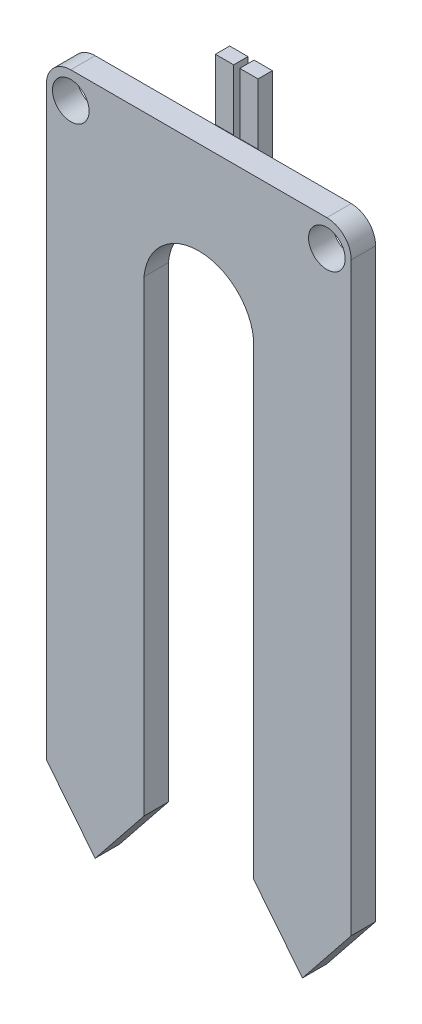
SolidWorks part; units mm, degrees
ref_plane "Front Plane" through (0, 0, 0) normal (0, 0, 1) x (1, 0, 0)
ref_plane "Top Plane" through (0, 0, 0) normal (0, 1, 0) x (1, 0, 0)
ref_plane "Right Plane" through (0, 0, 0) normal (1, 0, 0) x (0, 0, -1)
sketch "Sketch1" plane through (0, 0, 0) normal (0, 0, 1) x (1, 0, 0)
  line L0 (-31.9569, -21.6667) -> (-31.9569, 26.3333)
  line L1 (-29.9569, 28.3333) -> (-8.9569, 28.3333)
  line L2 (-6.9569, 26.3333) -> (-6.9569, -21.6667)
  line L5 (-14.9569, -21.6667) -> (-14.9569, 16.6279)
  line L7 (-23.9569, 16.6279) -> (-23.9569, -21.6667)
  line L10 (-23.9569, 28.3333) -> (-23.9569, 16.6279) construction
  line L11 (-27.9569, -21.6667) -> (-27.9569, -26.6667) construction
  line L12 (-31.9569, -21.6667) -> (-23.9569, -21.6667) construction
  line L13 (-14.9569, -21.6667) -> (-6.9569, -21.6667) construction
  line L14 (-10.9569, -21.6667) -> (-10.9569, -26.6667) construction
  line L15 (-31.9569, -21.6667) -> (-27.9569, -26.6667)
  line L16 (-27.9569, -26.6667) -> (-23.9569, -21.6667)
  line L17 (-14.9569, -21.6667) -> (-10.9569, -26.6667)
  line L18 (-10.9569, -26.6667) -> (-6.9569, -21.6667)
  arc A0 (-8.9569, 28.3333) -> (-6.9569, 26.3333) centre (-8.9569, 26.3333) cw
  arc A1 (-31.9569, 26.3333) -> (-29.9569, 28.3333) centre (-29.9569, 26.3333) cw
  arc A2 (-23.9569, 16.6279) -> (-14.9569, 16.6279) centre (-19.4569, 16.2026) cw
  point P15 (-6.9569, 28.3333)
  point P18 (-31.9569, 28.3333)
  point P20 (-23.4464, 16.6279)
  point P21 (-9.7982, 17.2627)
  point P22 (-9.9569, 16.6279)
  dimension "D8" = 2
  dimension "D1" = 50
  dimension "D2" = 25
  dimension "D3" = 50
  dimension "D4" = 5
  dimension "D5" = 8
  dimension "D6" = 8
  dimension "D7" = 5
  dimension "D9" = 8
extrude "Boss-Extrude1" add sketch "Sketch1" along normal blind 2
sketch "Sketch2" plane through (0, 0, 0) normal (0, 0, -1) x (-1, 0, 0)
  line L0 (6.9569, -21.6667) -> (6.9569, 26.3333) construction
  line L1 (31.9569, 26.3333) -> (31.9569, -21.6667) construction
  circle A0 centre (8.9569, 26.1469) radius 1.5
  circle A1 centre (29.9569, 26.1469) radius 1.5
  dimension "D1" = 3
  dimension "D2" = 3
  dimension "D3" = 2
  dimension "D4" = 2
extrude "Cut-Extrude1" cut sketch "Sketch2" against normal up to next
sketch "Sketch3" plane through (0, 0, 0) normal (0, 0, -1) x (-1, 0, 0)
  line L0 (19.4251, 27.5381) -> (19.4251, 26.0381)
  line L1 (17.4251, 27.5381) -> (18.9251, 27.5381)
  line L2 (17.4251, 27.5381) -> (17.4251, 26.0381)
  line L3 (17.4251, 26.0381) -> (18.9251, 26.0381)
  line L4 (18.9251, 27.5381) -> (18.9251, 26.0381)
  line L5 (19.4251, 27.5381) -> (20.9251, 27.5381)
  line L6 (20.9251, 27.5381) -> (20.9251, 26.0381)
  line L7 (19.4251, 26.0381) -> (20.9251, 26.0381)
  dimension "D1" = 1.5
  dimension "D2" = 1.5
  dimension "D3" = 2
extrude "Boss-Extrude2" add sketch "Sketch3" along normal blind 2
sketch "Sketch6" plane through (0, 27.5381, 0) normal (0, 1, 0) x (1, 0, 0)
  line L0 (-18.9251, 2) -> (-18.9251, 0.8285)
  line L1 (-20.9251, 2) -> (-19.4251, 2)
  line L2 (-20.9251, 2) -> (-20.9251, 0.8285)
  line L3 (-20.9251, 0.8285) -> (-19.4251, 0.8285)
  line L4 (-19.4251, 2) -> (-19.4251, 0.8285)
  line L5 (-18.9251, 2) -> (-17.4251, 2)
  line L6 (-17.4251, 2) -> (-17.4251, 0.8285)
  line L7 (-18.9251, 0.8285) -> (-17.4251, 0.8285)
  line L8 (-19.4251, 2) -> (-19.4251, 0) construction
  point P5 (-19.4251, 2)
  dimension "D1" = 2
extrude "Boss-Extrude5" add sketch "Sketch6" along normal blind 5
fillet "Fillet1" radius 0.2 2 edges at (-18.1751, 26.0381, -2) (-20.1751, 26.0381, -2)
sketch "Sketch7" plane through (0, 0, 0) normal (0, 0, -1) x (-1, 0, 0)
  line L0 (6.9569, 16.8604) -> (31.9569, 16.8604) construction
  line L1 (6.9569, -21.6667) -> (6.9569, 26.3333) construction
  line L2 (31.9569, 26.3333) -> (31.9569, -21.6667) construction
  line L3 (8.9569, 16.8604) -> (8.9569, 15.5723)
  line L5 (12.9569, -19.2207) -> (12.9569, -16.5552)
  line L6 (8.9569, 16.8604) -> (12.9569, 16.8604)
  line L28 (7.9941, 15.5723) -> (8.9569, 15.5723)
  line L30 (13.997, 13.4448) -> (12.9569, 13.4448)
  line L47 (7.9941, 9.5723) -> (8.9569, 9.5723)
  line L48 (13.997, 7.4448) -> (12.9569, 7.4448)
  line L49 (7.9941, 3.5723) -> (8.9569, 3.5723)
  line L50 (13.997, 1.4448) -> (12.9569, 1.4448)
  line L51 (7.9941, -2.4277) -> (8.9569, -2.4277)
  line L52 (13.997, -4.5552) -> (12.9569, -4.5552)
  line L53 (7.9941, -8.4277) -> (8.9569, -8.4277)
  line L54 (13.997, -10.5552) -> (12.9569, -10.5552)
  line L55 (7.9941, -14.4277) -> (8.9569, -14.4277)
  line L56 (13.997, -16.5552) -> (12.9569, -16.5552)
  line L57 (8.9569, 13.4448) -> (8.9569, 9.5723)
  line L58 (12.9569, 15.5723) -> (12.9569, 16.8604)
  line L59 (12.9569, 9.5723) -> (12.9569, 13.4448)
  line L60 (8.9569, 7.4448) -> (8.9569, 3.5723)
  line L61 (8.9569, 1.4448) -> (8.9569, -2.4277)
  line L62 (12.9569, 3.5723) -> (12.9569, 7.4448)
  line L63 (8.9569, -4.5552) -> (8.9569, -8.4277)
  line L64 (12.9569, -2.4277) -> (12.9569, 1.4448)
  line L65 (12.9569, -8.4277) -> (12.9569, -4.5552)
  line L66 (8.9569, -10.5552) -> (8.9569, -14.4277)
  line L67 (8.9569, -16.5552) -> (8.9569, -19.2207)
  line L68 (12.9569, -14.4277) -> (12.9569, -10.5552)
  line L69 (8.9569, -16.5552) -> (7.9941, -16.5552)
  line L70 (12.9569, -14.4277) -> (13.997, -14.4277)
  line L71 (8.9569, -10.5552) -> (7.9941, -10.5552)
  line L72 (12.9569, -8.4277) -> (13.997, -8.4277)
  line L73 (8.9569, -4.5552) -> (7.9941, -4.5552)
  line L74 (12.9569, -2.4277) -> (13.997, -2.4277)
  line L75 (8.9569, 1.4448) -> (7.9941, 1.4448)
  line L76 (12.9569, 3.5723) -> (13.997, 3.5723)
  line L77 (8.9569, 7.4448) -> (7.9941, 7.4448)
  line L78 (12.9569, 9.5723) -> (13.997, 9.5723)
  line L79 (8.9569, 13.4448) -> (7.9941, 13.4448)
  line L80 (12.9569, 15.5723) -> (13.997, 15.5723)
  line L81 (30.997, -16.5552) -> (29.9569, -16.5552)
  line L82 (29.9569, -19.2207) -> (29.9569, -16.5552)
  line L83 (25.9569, -16.5552) -> (25.9569, -19.2207)
  line L84 (25.9569, -16.5552) -> (24.9941, -16.5552)
  line L85 (24.9941, -14.4277) -> (25.9569, -14.4277)
  line L86 (25.9569, -10.5552) -> (25.9569, -14.4277)
  line L87 (25.9569, -10.5552) -> (24.9941, -10.5552)
  line L88 (24.9941, -8.4277) -> (25.9569, -8.4277)
  line L89 (25.9569, -4.5552) -> (25.9569, -8.4277)
  line L90 (25.9569, -4.5552) -> (24.9941, -4.5552)
  line L91 (24.9941, -2.4277) -> (25.9569, -2.4277)
  line L92 (25.9569, 1.4448) -> (25.9569, -2.4277)
  line L93 (25.9569, 1.4448) -> (24.9941, 1.4448)
  line L94 (24.9941, 3.5723) -> (25.9569, 3.5723)
  line L95 (25.9569, 7.4448) -> (25.9569, 3.5723)
  line L96 (25.9569, 7.4448) -> (24.9941, 7.4448)
  line L97 (24.9941, 9.5723) -> (25.9569, 9.5723)
  line L98 (25.9569, 13.4448) -> (25.9569, 9.5723)
  line L99 (25.9569, 13.4448) -> (24.9941, 13.4448)
  line L100 (24.9941, 15.5723) -> (25.9569, 15.5723)
  line L101 (25.9569, 16.8604) -> (25.9569, 15.5723)
  line L102 (25.9569, 16.8604) -> (29.9569, 16.8604)
  line L103 (29.9569, 15.5723) -> (29.9569, 16.8604)
  line L104 (29.9569, 15.5723) -> (30.997, 15.5723)
  line L105 (30.997, 13.4448) -> (29.9569, 13.4448)
  line L106 (29.9569, 9.5723) -> (29.9569, 13.4448)
  line L107 (29.9569, 9.5723) -> (30.997, 9.5723)
  line L108 (30.997, 7.4448) -> (29.9569, 7.4448)
  line L109 (29.9569, 3.5723) -> (29.9569, 7.4448)
  line L110 (29.9569, 3.5723) -> (30.997, 3.5723)
  line L111 (30.997, 1.4448) -> (29.9569, 1.4448)
  line L112 (29.9569, -2.4277) -> (29.9569, 1.4448)
  line L113 (29.9569, -2.4277) -> (30.997, -2.4277)
  line L114 (30.997, -4.5552) -> (29.9569, -4.5552)
  line L115 (29.9569, -8.4277) -> (29.9569, -4.5552)
  line L116 (29.9569, -8.4277) -> (30.997, -8.4277)
  line L117 (30.997, -10.5552) -> (29.9569, -10.5552)
  line L118 (29.9569, -14.4277) -> (29.9569, -10.5552)
  line L119 (29.9569, -14.4277) -> (30.997, -14.4277)
  arc A0 (8.9569, -19.2207) -> (12.9569, -19.2207) centre (10.9569, -19.2207) ccw
  arc A1 (7.9941, 15.5723) -> (7.9941, 13.4448) centre (9.0578, 14.5086) ccw
  arc A2 (13.997, 15.5723) -> (13.997, 13.4448) centre (12.9333, 14.5086) cw
  arc A3 (13.997, 9.5723) -> (13.997, 7.4448) centre (12.9333, 8.5086) cw
  arc A4 (7.9941, 9.5723) -> (7.9941, 7.4448) centre (9.0578, 8.5086) ccw
  arc A5 (13.997, 3.5723) -> (13.997, 1.4448) centre (12.9333, 2.5086) cw
  arc A6 (7.9941, 3.5723) -> (7.9941, 1.4448) centre (9.0578, 2.5086) ccw
  arc A7 (13.997, -2.4277) -> (13.997, -4.5552) centre (12.9333, -3.4914) cw
  arc A8 (7.9941, -2.4277) -> (7.9941, -4.5552) centre (9.0578, -3.4914) ccw
  arc A9 (13.997, -8.4277) -> (13.997, -10.5552) centre (12.9333, -9.4914) cw
  arc A10 (7.9941, -8.4277) -> (7.9941, -10.5552) centre (9.0578, -9.4914) ccw
  arc A11 (13.997, -14.4277) -> (13.997, -16.5552) centre (12.9333, -15.4914) cw
  arc A12 (7.9941, -14.4277) -> (7.9941, -16.5552) centre (9.0578, -15.4914) ccw
  arc A13 (25.9569, -19.2207) -> (29.9569, -19.2207) centre (27.9569, -19.2207) ccw
  arc A14 (24.9941, -14.4277) -> (24.9941, -16.5552) centre (26.0578, -15.4914) ccw
  arc A15 (24.9941, -8.4277) -> (24.9941, -10.5552) centre (26.0578, -9.4914) ccw
  arc A16 (24.9941, -2.4277) -> (24.9941, -4.5552) centre (26.0578, -3.4914) ccw
  arc A17 (24.9941, 3.5723) -> (24.9941, 1.4448) centre (26.0578, 2.5086) ccw
  arc A18 (24.9941, 9.5723) -> (24.9941, 7.4448) centre (26.0578, 8.5086) ccw
  arc A19 (24.9941, 15.5723) -> (24.9941, 13.4448) centre (26.0578, 14.5086) ccw
  arc A20 (30.997, 15.5723) -> (30.997, 13.4448) centre (29.9333, 14.5086) cw
  arc A21 (30.997, 9.5723) -> (30.997, 7.4448) centre (29.9333, 8.5086) cw
  arc A22 (30.997, 3.5723) -> (30.997, 1.4448) centre (29.9333, 2.5086) cw
  arc A23 (30.997, -2.4277) -> (30.997, -4.5552) centre (29.9333, -3.4914) cw
  arc A24 (30.997, -8.4277) -> (30.997, -10.5552) centre (29.9333, -9.4914) cw
  arc A25 (30.997, -14.4277) -> (30.997, -16.5552) centre (29.9333, -15.4914) cw
  dimension "D1" = 4
  dimension "D2" = 2
  dimension "D3" = 6
  dimension "D4" = 2
extrude "Boss-Extrude6" add sketch "Sketch7" along normal blind 0.3
